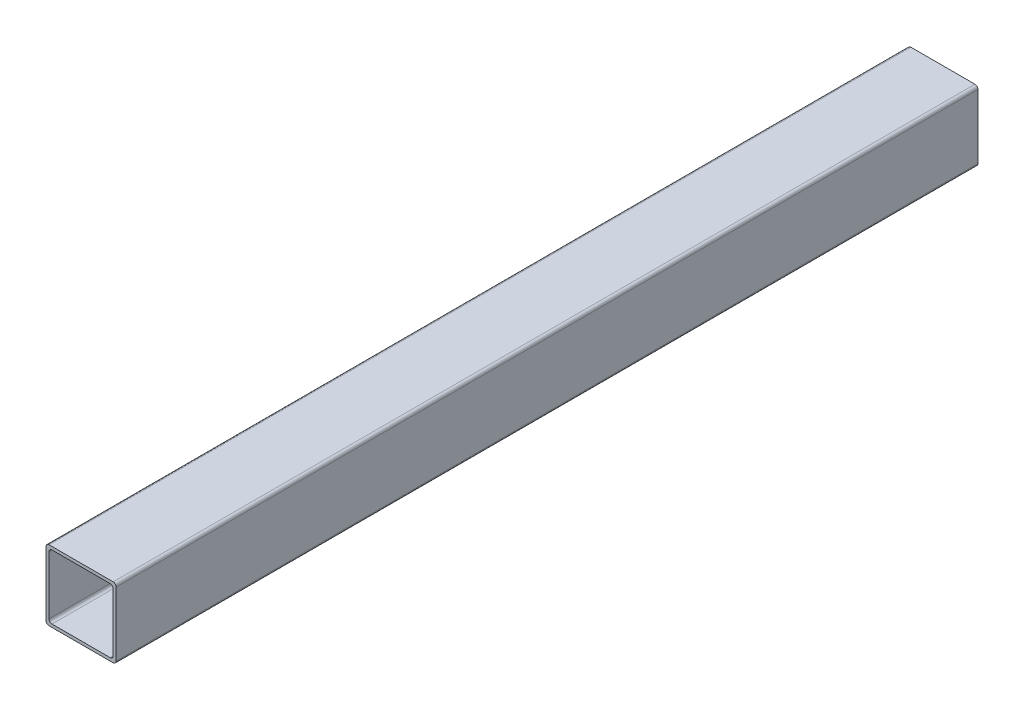
SolidWorks part; units mm, degrees
ref_plane "Front Plane" through (0, 0, 0) normal (0, 0, 1) x (1, 0, 0)
ref_plane "Top Plane" through (0, 0, 0) normal (0, 1, 0) x (1, 0, 0)
ref_plane "Right Plane" through (0, 0, 0) normal (1, 0, 0) x (0, 0, -1)
sketch "Sketch1" plane through (0, 0, 0) normal (0, 0, 1) x (1, 0, 0)
  line L0 (3, 67) -> (67, 67)
  line L1 (0, 0) -> (70, 0)
  line L2 (0, 0) -> (0, 70)
  line L3 (0, 70) -> (70, 70)
  line L4 (70, 0) -> (70, 70)
  line L5 (67, 3) -> (67, 67)
  line L6 (3, 3) -> (67, 3)
  line L7 (3, 3) -> (3, 67)
  dimension "D1" = 70
  dimension "D2" = 70
  dimension "D3" = 3
extrude "Boss-Extrude1" add sketch "Sketch1" along normal blind 860
fillet "Fillet1" radius 3 8 edges at (70, 0, 430) (67, 3, 430) (70, 70, 430) (67, 67, 430) (0, 70, 430) (3, 67, 430) (3, 3, 430) (0, 0, 430)
